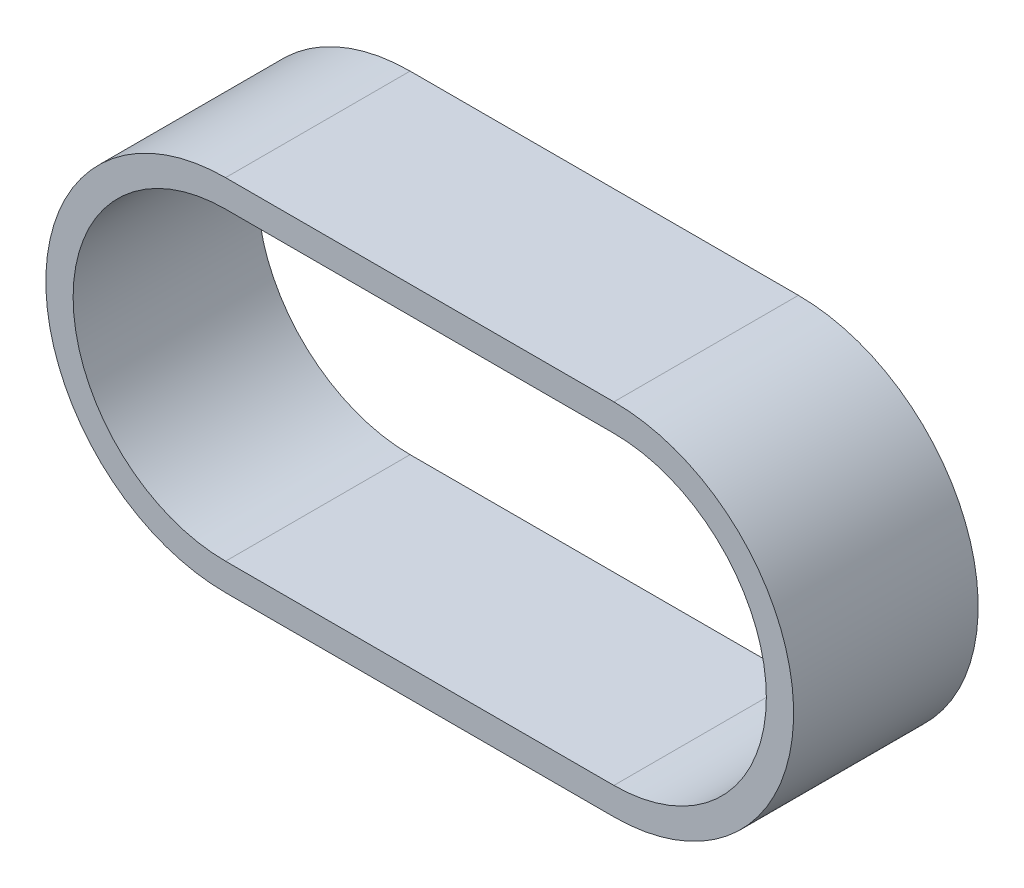
SolidWorks part; units mm, degrees
material "A2432/ Gomma"
ref_plane "Piano frontale" through (0, 0, 0) normal (0, 0, 1) x (1, 0, 0)
ref_plane "Piano superiore" through (0, 0, 0) normal (0, 1, 0) x (1, 0, 0)
ref_plane "Piano destro" through (0, 0, 0) normal (1, 0, 0) x (0, 0, -1)
sketch "Schizzo1" plane through (0, 0, 0) normal (0, 0, 1) x (1, 0, 0)
  line L0 (-121, 0) -> (121, 0) construction
  line L1 (-121, 95) -> (121, 95)
  line L2 (-121, -95) -> (121, -95)
  line L3 (-121, 0) -> (121, 0) construction
  line L4 (-121, 112) -> (121, 112)
  line L5 (-121, -112) -> (121, -112)
  arc A0 (-121, 95) -> (-121, -95) centre (-121, 0) ccw
  arc A1 (121, -95) -> (121, 95) centre (121, 0) ccw
  arc A2 (-121, 112) -> (-121, -112) centre (-121, 0) ccw
  arc A3 (121, -112) -> (121, 112) centre (121, 0) ccw
  point P2 (0, 0)
  point P7 (0, 0)
  dimension "D1" = 242
  dimension "D2" = 190
  dimension "D3" = 17
extrude "Estrusione-Estrusione1" add sketch "Schizzo1" along normal blind 115
ref_plane "Piano1" through (0, 0, 67.5) normal (0, 0, 1) x (1, 0, 0)
ref_plane "Piano2" through (0, 0, 47.5) normal (0, 0, 1) x (1, 0, 0)
